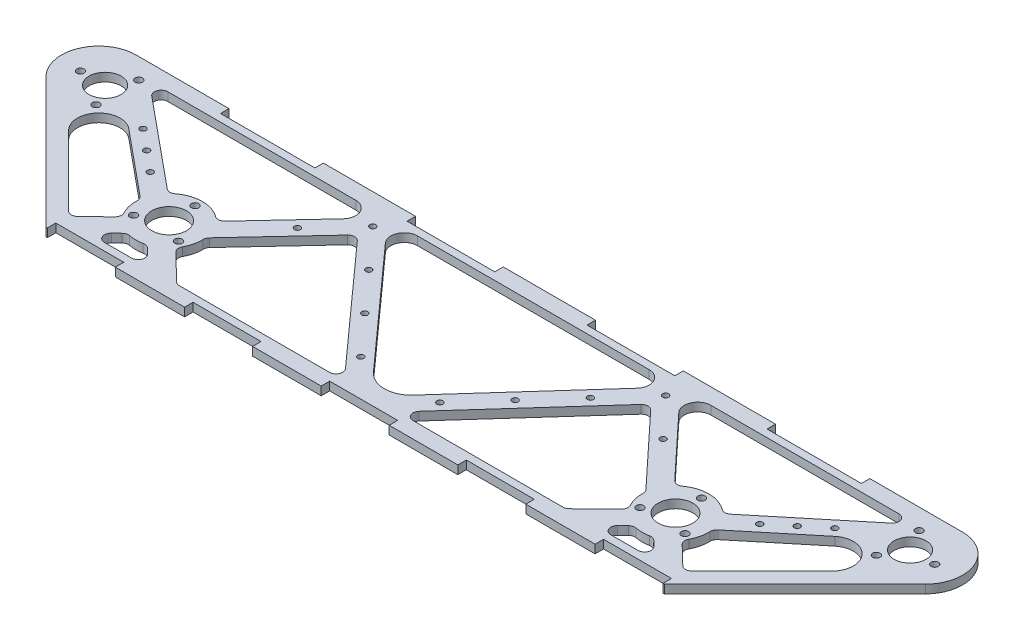
SolidWorks part; units mm, degrees
material "6061-T6 (SS)"
ref_plane "Alzado" through (0, 0, 0) normal (0, 0, 1) x (1, 0, 0)
ref_plane "Planta" through (0, 0, 0) normal (0, 1, 0) x (1, 0, 0)
ref_plane "Vista lateral" through (0, 0, 0) normal (1, 0, 0) x (0, 0, -1)
sketch "Sketch1" plane through (0, 0, 0) normal (0, 1, 0) x (1, 0, 0)
  line L0 (-232.01, 0) -> (232.01, 0)
  line L1 (-232.01, 0) -> (-329.8939, 97.8839)
  line L2 (-310.0879, 145.7) -> (310.0879, 145.7)
  line L3 (329.8939, 97.8839) -> (232.01, 0)
  line L4 (-310.0879, 135.7) -> (310.0879, 135.7) construction
  line L5 (322.8229, 104.955) -> (227.8679, 10) construction
  line L6 (-227.8679, 10) -> (227.8679, 10) construction
  line L7 (-227.8679, 10) -> (-322.8229, 104.955) construction
  arc A0 (310.0879, 145.7) -> (329.8939, 97.8839) centre (310.0879, 117.69) cw
  arc A1 (-329.8939, 97.8839) -> (-310.0879, 145.7) centre (-310.0879, 117.69) cw
  arc A2 (310.0879, 135.7) -> (322.8229, 104.955) centre (310.0879, 117.69) cw construction
  arc A3 (-322.8229, 104.955) -> (-310.0879, 135.7) centre (-310.0879, 117.69) cw construction
  point P4 (0, 0)
  dimension "D4" = 28.01
  dimension "D1" = 45
  dimension "D2" = 464.02
  dimension "D3" = 145.7
  dimension "D5" = 10
extrude "Boss-Extrude1" add sketch "Sketch1" along normal blind 6.35
sketch "Sketch2" plane through (0, 6.35, 0) normal (0, 1, 0) x (1, 0, 0)
  line L0 (310.0879, 145.7) -> (-310.0879, 145.7) construction
  line L1 (0, 0) -> (0, 145.7) construction
  line L2 (-232.01, 0) -> (232.01, 0) construction
  circle A0 centre (-302.0235, 114.35) radius 12
  circle A2 centre (-190, 50.35) radius 13
  circle A5 centre (-302.0235, 114.35) radius 18.5 construction
  circle A6 centre (-190, 50.35) radius 19.5 construction
  circle A7 centre (-320.5235, 114.35) radius 2.75
  circle A8 centre (-292.7735, 130.3715) radius 2.75
  circle A9 centre (-292.7735, 98.3285) radius 2.75
  circle A11 centre (-190, 69.85) radius 2.75
  circle A12 centre (-173.1125, 40.6) radius 2.75
  circle A13 centre (-206.8875, 40.6) radius 2.75
  circle A14 centre (190, 50.35) radius 19.5 construction
  circle A15 centre (302.0235, 114.35) radius 18.5 construction
  circle A16 centre (206.8875, 40.6) radius 2.75
  circle A17 centre (173.1125, 40.6) radius 2.75
  circle A18 centre (190, 69.85) radius 2.75
  circle A19 centre (292.7735, 98.3285) radius 2.75
  circle A20 centre (292.7735, 130.3715) radius 2.75
  circle A21 centre (320.5235, 114.35) radius 2.75
  circle A22 centre (190, 50.35) radius 13
  circle A23 centre (302.0235, 114.35) radius 12
  point P29 (-190, 50.35)
  point P30 (-302.0235, 114.35)
  point P49 (302.0235, 114.35)
  point P50 (190, 50.35)
  dimension "D3" = 24
  dimension "D6" = 26
  dimension "D7" = 37
  dimension "D8" = 39
  dimension "D9" = 5.5
  dimension "D11" = 3
  dimension "D2" = 31.35
  dimension "D4" = 50.35
  dimension "D5" = 42.01
  dimension "D12" = 604.047
  dimension "D10" = 3
extrude "Cut-Extrude1" cut sketch "Sketch2" against normal blind 10
sketch "Sketch4" plane through (0, 6.35, 0) normal (0, 1, 0) x (1, 0, 0)
  line L12 (229.3797, 6.35) -> (325.4038, 102.3741)
  line L13 (310.0879, 139.35) -> (-310.0879, 139.35)
  line L14 (-325.4038, 102.3741) -> (-229.3797, 6.35)
  line L15 (-229.3797, 6.35) -> (229.3797, 6.35)
  line L16 (229.3797, 6.35) -> (325.4038, 102.3741) construction
  line L17 (310.0879, 139.35) -> (-310.0879, 139.35) construction
  line L18 (-325.4038, 102.3741) -> (-229.3797, 6.35) construction
  line L19 (-229.3797, 6.35) -> (229.3797, 6.35) construction
  arc A6 (325.4038, 102.3741) -> (310.0879, 139.35) centre (310.0879, 117.69) ccw
  arc A7 (-310.0879, 139.35) -> (-325.4038, 102.3741) centre (-310.0879, 117.69) ccw
  arc A8 (325.4038, 102.3741) -> (310.0879, 139.35) centre (310.0879, 117.69) ccw construction
  arc A9 (-310.0879, 139.35) -> (-325.4038, 102.3741) centre (-310.0879, 117.69) ccw construction
  dimension "D1" = 6.35
sketch "Sketch3" plane through (0, 6.35, 0) normal (0, 1, 0) x (1, 0, 0)
  line L0 (-203.6098, 20.5948) -> (-199.5103, 24.558)
  line L1 (-180.4897, 24.558) -> (-176.3902, 20.5948)
  line L2 (-216.7974, 55.3714) -> (-264.9333, 95.0444)
  line L3 (-226.9661, 18.8783) -> (-212.9059, 32.4713)
  line L4 (-211.3773, 70.3424) -> (-277.5023, 124.8416)
  line L5 (-274.3223, 133.7) -> (-133.2758, 133.7)
  line L6 (-168.6307, 71.1511) -> (-125.9643, 116.8778)
  line L7 (0, 12) -> (0, 133.7) construction
  line L8 (-94.3432, 117.0171) -> (-14.878, 28.5613)
  line L9 (227.0394, 12) -> (321.4087, 106.3692)
  line L10 (310.0879, 133.7) -> (-310.0879, 133.7)
  line L11 (-321.4087, 106.3692) -> (-227.0394, 12)
  line L12 (-227.0394, 12) -> (227.0394, 12)
  line L13 (227.0394, 12) -> (321.4087, 106.3692) construction
  line L14 (310.0879, 133.7) -> (133.2758, 133.7) construction
  line L15 (-321.4087, 106.3692) -> (-227.0394, 12) construction
  line L16 (-227.0394, 12) -> (227.0394, 12) construction
  line L17 (-167.0941, 32.4713) -> (-147.3727, 13.4052)
  line L18 (-163.6645, 54.4864) -> (-113.7257, 108.0071)
  line L19 (-106.3504, 107.9375) -> (-27.6576, 20.3415)
  line L20 (-286.4232, 71.3837) -> (-233.977, 18.9375)
  line L21 (-200.1345, 12) -> (-179.8655, 12)
  line L22 (-143.8974, 12) -> (-31.3771, 12)
  line L23 (-86.9042, 133.7) -> (86.9042, 133.7)
  line L24 (143.8974, 12) -> (31.3771, 12)
  line L25 (200.1345, 12) -> (179.8655, 12)
  line L26 (286.4232, 71.3837) -> (233.977, 18.9375)
  line L27 (106.3504, 107.9375) -> (27.6576, 20.3415)
  line L28 (163.6645, 54.4864) -> (113.7257, 108.0071)
  line L29 (167.0941, 32.4713) -> (147.3727, 13.4052)
  line L30 (94.3432, 117.0171) -> (14.878, 28.5613)
  line L31 (168.6307, 71.1511) -> (125.9643, 116.8778)
  line L32 (274.3223, 133.7) -> (133.2758, 133.7)
  line L33 (211.3773, 70.3424) -> (277.5023, 124.8416)
  line L34 (226.9661, 18.8783) -> (212.9059, 32.4713)
  line L35 (216.7974, 55.3714) -> (264.9333, 95.0444)
  line L36 (180.4897, 24.558) -> (176.3902, 20.5948)
  line L37 (203.6098, 20.5948) -> (199.5103, 24.558)
  line L38 (-133.2758, 133.7) -> (-310.0879, 133.7) construction
  line L39 (86.9042, 133.7) -> (-86.9042, 133.7) construction
  arc A0 (-214.9812, 51.3192) -> (-211.9843, 38.4467) centre (-190, 50.35) ccw
  arc A1 (-264.9333, 95.0444) -> (-286.4232, 71.3837) centre (-275.1095, 82.6975) ccw
  arc A2 (-277.5023, 124.8416) -> (-274.3223, 133.7) centre (-274.3223, 128.7) cw
  arc A3 (-175.2387, 70.5268) -> (-205.1644, 70.2256) centre (-190, 50.35) ccw
  arc A4 (321.4087, 106.3692) -> (310.0879, 133.7) centre (310.0879, 117.69) ccw
  arc A5 (-310.0879, 133.7) -> (-321.4087, 106.3692) centre (-310.0879, 117.69) ccw
  arc A6 (321.4087, 106.3692) -> (310.0879, 133.7) centre (310.0879, 117.69) ccw construction
  arc A7 (-310.0879, 133.7) -> (-321.4087, 106.3692) centre (-310.0879, 117.69) ccw construction
  arc A8 (-168.0157, 38.4467) -> (-165.0073, 50.9544) centre (-190, 50.35) ccw
  arc A9 (-195.0292, 25.8611) -> (-184.9708, 25.8611) centre (-190, 50.35) ccw
  arc A10 (195.0292, 25.8611) -> (184.9708, 25.8611) centre (190, 50.35) cw
  arc A11 (168.0157, 38.4467) -> (165.0073, 50.9544) centre (190, 50.35) cw
  arc A12 (175.2387, 70.5268) -> (205.1644, 70.2256) centre (190, 50.35) cw
  arc A13 (277.5023, 124.8416) -> (274.3223, 133.7) centre (274.3223, 128.7) ccw
  arc A14 (264.9333, 95.0444) -> (286.4232, 71.3837) centre (275.1095, 82.6975) cw
  arc A15 (214.9812, 51.3192) -> (211.9843, 38.4467) centre (190, 50.35) cw
  arc A16 (-133.2758, 133.7) -> (-125.9643, 116.8778) centre (-133.2758, 123.7) cw
  arc A17 (-94.3432, 117.0171) -> (-86.9042, 133.7) centre (-86.9042, 123.7) cw
  arc A18 (94.3432, 117.0171) -> (86.9042, 133.7) centre (86.9042, 123.7) ccw
  arc A19 (125.9643, 116.8778) -> (133.2758, 133.7) centre (133.2758, 123.7) cw
  arc A20 (-175.2387, 70.5268) -> (-168.6307, 71.1511) centre (-172.2865, 74.5622) ccw
  arc A21 (-211.3773, 70.3424) -> (-205.1644, 70.2256) centre (-208.1973, 74.2008) ccw
  arc A22 (-216.7974, 55.3714) -> (-214.9812, 51.3192) centre (-219.9774, 51.513) cw
  arc A23 (-212.9059, 32.4713) -> (-211.9843, 38.4467) centre (-216.3812, 36.066) ccw
  arc A24 (-226.9661, 18.8783) -> (-233.977, 18.9375) centre (-230.4414, 22.4731) cw
  arc A25 (-203.6098, 20.5948) -> (-200.1345, 12) centre (-200.1345, 17) ccw
  arc A26 (-199.5103, 24.558) -> (-195.0292, 25.8611) centre (-196.035, 20.9633) cw
  arc A27 (-180.4897, 24.558) -> (-184.9708, 25.8611) centre (-183.965, 20.9633) ccw
  arc A28 (-176.3902, 20.5948) -> (-179.8655, 12) centre (-179.8655, 17) cw
  arc A29 (-113.7257, 108.0071) -> (-106.3504, 107.9375) centre (-110.0699, 104.596) cw
  arc A30 (-163.6645, 54.4864) -> (-165.0073, 50.9544) centre (-160.0088, 51.0753) ccw
  arc A31 (-167.0941, 32.4713) -> (-168.0157, 38.4467) centre (-163.6188, 36.066) cw
  arc A32 (-147.3727, 13.4052) -> (-143.8974, 12) centre (-143.8974, 17) ccw
  arc A33 (179.8655, 12) -> (176.3902, 20.5948) centre (179.8655, 17) cw
  arc A34 (184.9708, 25.8611) -> (180.4897, 24.558) centre (183.965, 20.9633) ccw
  arc A35 (195.0292, 25.8611) -> (199.5103, 24.558) centre (196.035, 20.9633) cw
  arc A36 (200.1345, 12) -> (203.6098, 20.5948) centre (200.1345, 17) ccw
  arc A37 (233.977, 18.9375) -> (226.9661, 18.8783) centre (230.4414, 22.4731) cw
  arc A38 (214.9812, 51.3192) -> (216.7974, 55.3714) centre (219.9774, 51.513) cw
  arc A39 (211.9843, 38.4467) -> (212.9059, 32.4713) centre (216.3812, 36.066) ccw
  arc A40 (175.2387, 70.5268) -> (168.6307, 71.1511) centre (172.2865, 74.5622) cw
  arc A41 (205.1644, 70.2256) -> (211.3773, 70.3424) centre (208.1973, 74.2008) ccw
  arc A42 (106.3504, 107.9375) -> (113.7257, 108.0071) centre (110.0699, 104.596) cw
  arc A43 (165.0073, 50.9544) -> (163.6645, 54.4864) centre (160.0088, 51.0753) ccw
  arc A44 (168.0157, 38.4467) -> (167.0941, 32.4713) centre (163.6188, 36.066) cw
  arc A45 (143.8974, 12) -> (147.3727, 13.4052) centre (143.8974, 17) ccw
  arc A46 (31.3771, 12) -> (27.6576, 20.3415) centre (31.3771, 17) cw
  arc A47 (-27.6576, 20.3415) -> (-31.3771, 12) centre (-31.3771, 17) cw
  arc A49 (-14.878, 28.5613) -> (14.878, 28.5613) centre (0, 41.9271) ccw
  point P72 (-171.9247, 67.6209)
  point P75 (-208.0753, 67.6209)
  point P78 (-214.774, 53.7038)
  point P81 (-209.9698, 35.3098)
  point P84 (-230.5007, 15.4612)
  point P87 (-212.5, 12)
  point P90 (-197.5, 26.5015)
  point P93 (-182.5, 26.5015)
  point P96 (-167.5, 12)
  point P99 (-110, 112)
  point P102 (-165.1318, 52.9138)
  point P105 (-170.0302, 35.3098)
  point P108 (-145.9191, 12)
  point P111 (167.5, 12)
  point P114 (182.5, 26.5015)
  point P117 (197.5, 26.5015)
  point P120 (212.5, 12)
  point P123 (230.5007, 15.4612)
  point P126 (214.774, 53.7038)
  point P129 (209.9698, 35.3098)
  point P132 (171.9247, 67.6209)
  point P135 (208.0753, 67.6209)
  point P138 (110, 112)
  point P141 (165.1318, 52.9138)
  point P144 (170.0302, 35.3098)
  point P147 (145.9191, 12)
  point P150 (20.164, 12)
  point P153 (-20.164, 12)
  dimension "D2" = 50
  dimension "D3" = 5
  dimension "D4" = 15
  dimension "D11" = 18.394
  dimension "D8" = 16
  dimension "D15" = 10
  dimension "D16" = 10
  dimension "D17" = 10
  dimension "D18" = 10
  dimension "D20" = 5
  dimension "D21" = 20
  dimension "D5" = 15
  dimension "D6" = 15
  dimension "D7" = 45
  dimension "D9" = 220
  dimension "D10" = 15
  dimension "D12" = 15
  dimension "D13" = 15
  dimension "D14" = 65
  dimension "D19" = 100
  dimension "D1" = 12
extrude "Cut-Extrude4" cut sketch "Sketch3" against normal blind 10
sketch "Sketch5" plane through (0, 6.35, 0) normal (0, 1, 0) x (1, 0, 0)
  line L0 (-232.01, 0) -> (232.01, 0) construction
  line L1 (-231.01, 0) -> (232.01, 0) construction
  line L2 (-231.01, 0) -> (-231.01, 6.36) construction
  line L3 (-231.01, 6.36) -> (232.01, 6.36) construction
  line L4 (232.01, 0) -> (232.01, 6.36) construction
  line L5 (-231.01, 6.36) -> (-180.01, 6.36)
  line L6 (-231.01, 6.36) -> (-231.01, 0)
  line L7 (-231.01, 0) -> (-180.01, 0)
  line L8 (-180.01, 6.36) -> (-180.01, 0)
  line L9 (-25.5, 6.36) -> (25.5, 6.36)
  line L10 (-25.5, 6.36) -> (-25.5, 0)
  line L11 (-25.5, 0) -> (25.5, 0)
  line L12 (25.5, 6.36) -> (25.5, 0)
  line L13 (-128.01, 6.36) -> (-77.01, 6.36)
  line L14 (-128.01, 6.36) -> (-128.01, 0)
  line L15 (-128.01, 0) -> (-77.01, 0)
  line L16 (-77.01, 6.36) -> (-77.01, 0)
  line L17 (0, 0) -> (0, 6.36) construction
  line L23 (77.01, 6.36) -> (128.01, 6.36)
  line L24 (77.01, 6.36) -> (77.01, 0)
  line L25 (77.01, 0) -> (128.01, 0)
  line L26 (128.01, 6.36) -> (128.01, 0)
  line L27 (180.01, 6.36) -> (231.01, 6.36)
  line L28 (180.01, 6.36) -> (180.01, 0)
  line L29 (180.01, 0) -> (231.01, 0)
  line L30 (231.01, 6.36) -> (231.01, 0)
  dimension "D1" = 6.36
  dimension "D2" = 51
  dimension "D3" = 51
  dimension "D4" = 25.5
  dimension "D5" = 51
  dimension "D6" = 52
  dimension "D7" = 51.51
  dimension "D8" = 51
  dimension "D9" = 51
  dimension "D10" = 1
  dimension "D11" = 51.51
  dimension "D12" = 1
  dimension "D13" = 52
extrude "Cut-Extrude5" cut sketch "Sketch5" against normal blind 10
sketch "Sketch6" plane through (0, 6.35, 0) normal (0, 1, 0) x (1, 0, 0)
  line L0 (-309.99, 139.34) -> (309.99, 139.34) construction
  line L1 (310.0879, 145.7) -> (-310.0879, 145.7) construction
  line L3 (-309.99, 139.34) -> (-239.99, 139.34) construction
  line L4 (-309.99, 139.34) -> (-309.99, 145.7) construction
  line L5 (-309.99, 145.7) -> (-239.99, 145.7) construction
  line L6 (-239.99, 139.34) -> (-239.99, 145.7) construction
  line L7 (-309.99, 139.34) -> (-239.99, 145.7) construction
  line L8 (-309.99, 145.7) -> (-239.99, 139.34) construction
  line L9 (-169.99, 145.7) -> (-99.99, 145.7) construction
  line L10 (-169.99, 145.7) -> (-169.99, 139.34) construction
  line L11 (-169.99, 139.34) -> (-99.99, 139.34) construction
  line L12 (-99.99, 145.7) -> (-99.99, 139.34) construction
  line L13 (-169.99, 145.7) -> (-99.99, 139.34) construction
  line L14 (-169.99, 139.34) -> (-99.99, 145.7) construction
  line L15 (-35, 145.7) -> (35, 145.7) construction
  line L16 (-35, 145.7) -> (-35, 139.34) construction
  line L17 (-35, 139.34) -> (35, 139.34) construction
  line L18 (35, 145.7) -> (35, 139.34) construction
  line L19 (-35, 145.7) -> (35, 139.34) construction
  line L20 (-35, 139.34) -> (35, 145.7) construction
  line L21 (310.0879, 145.7) -> (240.0879, 145.7) construction
  line L22 (310.0879, 145.7) -> (310.0879, 139.34) construction
  line L23 (310.0879, 139.34) -> (240.0879, 139.34) construction
  line L24 (240.0879, 145.7) -> (240.0879, 139.34) construction
  line L25 (310.0879, 145.7) -> (240.0879, 139.34) construction
  line L26 (310.0879, 139.34) -> (240.0879, 145.7) construction
  line L27 (170.0879, 145.7) -> (100.0879, 145.7) construction
  line L28 (170.0879, 145.7) -> (170.0879, 139.34) construction
  line L29 (170.0879, 139.34) -> (100.0879, 139.34) construction
  line L30 (100.0879, 145.7) -> (100.0879, 139.34) construction
  line L31 (170.0879, 145.7) -> (100.0879, 139.34) construction
  line L32 (170.0879, 139.34) -> (100.0879, 145.7) construction
  line L33 (-240.39, 145.7) -> (-169.59, 145.7)
  line L34 (-240.39, 145.7) -> (-240.39, 139.34)
  line L35 (-240.39, 139.34) -> (-169.59, 139.34)
  line L36 (-169.59, 145.7) -> (-169.59, 139.34)
  line L37 (-240.39, 145.7) -> (-169.59, 139.34) construction
  line L38 (-240.39, 139.34) -> (-169.59, 145.7) construction
  line L39 (-100.39, 145.7) -> (-34.6, 145.7)
  line L40 (-100.39, 145.7) -> (-100.39, 139.34)
  line L41 (-100.39, 139.34) -> (-34.6, 139.34)
  line L42 (-34.6, 145.7) -> (-34.6, 139.34)
  line L43 (-100.39, 145.7) -> (-34.6, 139.34) construction
  line L44 (-100.39, 139.34) -> (-34.6, 145.7) construction
  line L45 (34.6, 145.7) -> (100.4879, 145.7)
  line L46 (34.6, 145.7) -> (34.6, 139.34)
  line L47 (34.6, 139.34) -> (100.4879, 139.34)
  line L48 (100.4879, 145.7) -> (100.4879, 139.34)
  line L49 (34.6, 145.7) -> (100.4879, 139.34) construction
  line L50 (34.6, 139.34) -> (100.4879, 145.7) construction
  line L51 (169.6879, 145.7) -> (240.4879, 145.7)
  line L52 (169.6879, 145.7) -> (169.6879, 139.34)
  line L53 (169.6879, 139.34) -> (240.4879, 139.34)
  line L54 (240.4879, 145.7) -> (240.4879, 139.34)
  line L55 (169.6879, 145.7) -> (240.4879, 139.34) construction
  line L56 (169.6879, 139.34) -> (240.4879, 145.7) construction
  point P3 (0, 139.34)
  point P11 (-274.99, 142.52)
  point P14 (-134.99, 142.52)
  point P19 (0, 142.52)
  point P25 (275.0879, 142.52)
  point P30 (135.0879, 142.52)
  point P35 (-204.99, 142.52)
  point P40 (-67.495, 142.52)
  point P45 (67.5439, 142.52)
  point P50 (205.0879, 142.52)
  dimension "D1" = 6.36
  dimension "D2" = 70
  dimension "D3" = 70
  dimension "D4" = 70
  dimension "D5" = 70
  dimension "D6" = 619.98
  dimension "D7" = 70
  dimension "D8" = 70
  dimension "D9" = 70
  dimension "D10" = 0.4
  dimension "D11" = 0.4
  dimension "D12" = 0.4
  dimension "D13" = 0.4
  dimension "D14" = 0.4
  dimension "D15" = 0.4
  dimension "D16" = 0.4
  dimension "D17" = 0.4
extrude "Cut-Extrude6" cut sketch "Sketch6" against normal blind 10
sketch "Sketch7" plane through (0, 6.35, 0) normal (0, 1, 0) x (1, 0, 0)
  line L0 (-169.59, 145.7) -> (-169.59, 185.7)
  line L1 (-149.59, 185.7) -> (-149.59, 145.7)
  line L2 (-100.39, 145.7) -> (-169.59, 145.7) construction
  line L3 (-159.59, 185.7) -> (-159.59, 155.7) construction
  line L4 (-156.59, 185.7) -> (-156.59, 155.7)
  line L5 (-162.59, 185.7) -> (-162.59, 155.7)
  line L6 (-169.59, 145.7) -> (-149.59, 145.7)
  arc A0 (-169.59, 185.7) -> (-149.59, 185.7) centre (-159.59, 185.7) cw
  arc A1 (-156.59, 185.7) -> (-162.59, 185.7) centre (-159.59, 185.7) ccw
  arc A2 (-162.59, 155.7) -> (-156.59, 155.7) centre (-159.59, 155.7) ccw
  point P5 (-159.59, 170.7)
  dimension "D1" = 20
  dimension "D2" = 40
  dimension "D3" = 6
  dimension "D4" = 30
extrude "Boss-Extrude2" [suppressed] add sketch "Sketch7" against normal through all
mirror "Mirror1" [suppressed] about plane through (0, 0, 0) normal (1, 0, 0)
sketch "Sketch8" plane through (0, 6.35, 0) normal (0, 1, 0) x (1, 0, 0)
  circle A0 centre (259.5529, 100.3289) radius 2.25
  circle A1 centre (244.1193, 87.6088) radius 2.25
  circle A2 centre (228.6856, 74.8886) radius 2.25
  circle A3 centre (137.1838, 93.86) radius 2.25
  circle A4 centre (109.8951, 123.1059) radius 2.25
  circle A5 centre (83.1635, 93.3499) radius 2.25
  circle A6 centre (56.4319, 63.5939) radius 2.25
  circle A7 centre (29.7003, 33.8379) radius 2.25
  circle A8 centre (-29.7003, 33.8379) radius 2.25
  circle A9 centre (-56.4319, 63.5939) radius 2.25
  circle A10 centre (-83.1635, 93.3499) radius 2.25
  circle A11 centre (-109.8951, 123.1059) radius 2.25
  circle A12 centre (-137.1838, 93.86) radius 2.25
  circle A13 centre (-228.6856, 74.8886) radius 2.25
  circle A14 centre (-244.1193, 87.6088) radius 2.25
  circle A15 centre (-259.5529, 100.3289) radius 2.25
  dimension "D1" = 4.5
extrude "Cut-Extrude7" cut sketch "Sketch8" against normal up to surface (6.35 mm away) up to face at (0.014, 0, -67.7219)
